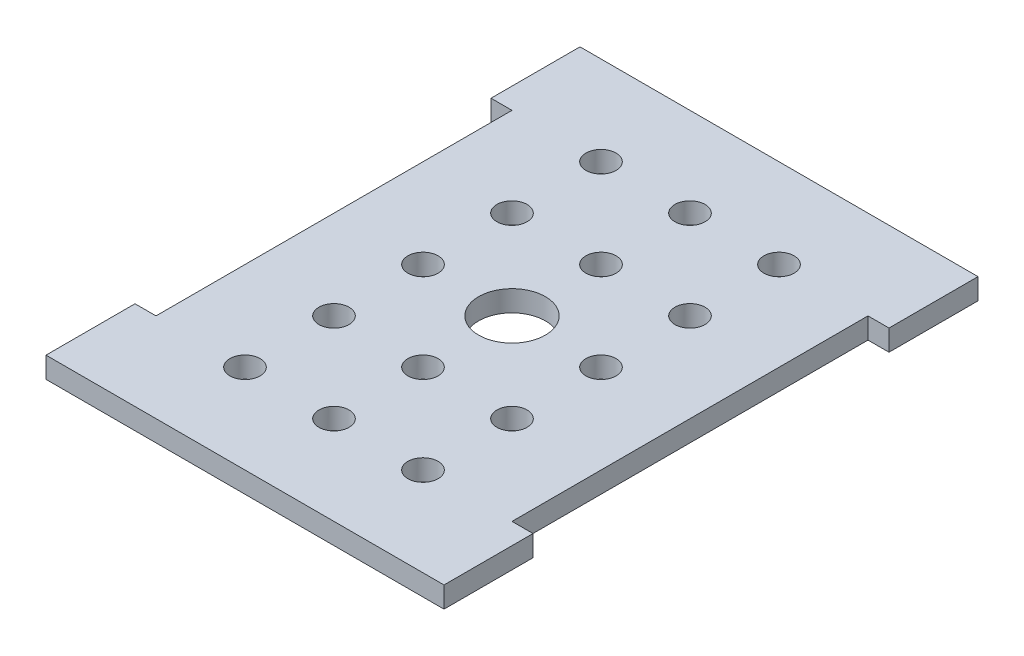
SolidWorks part; units mm, degrees
material "Custom Plastic"
ref_plane "Front Plane" through (0, 0, 0) normal (0, 0, 1) x (1, 0, 0)
ref_plane "Top Plane" through (0, 0, 0) normal (0, 1, 0) x (1, 0, 0)
ref_plane "Right Plane" through (0, 0, 0) normal (1, 0, 0) x (0, 0, -1)
sketch "Sketch1" plane through (0, 0, 0) normal (0, 1, 0) x (1, 0, 0)
  line L1 (-25.4, -38.1) -> (25.4, -38.1)
  line L2 (-25.4, -38.1) -> (-25.4, 38.1)
  line L3 (-25.4, 38.1) -> (25.4, 38.1)
  line L4 (25.4, -38.1) -> (25.4, 38.1)
  line L5 (-25.4, -38.1) -> (25.4, 38.1) construction
  line L6 (-25.4, 38.1) -> (25.4, -38.1) construction
  point P0 (0, 0)
  dimension "D1" = 50.8
  dimension "D2" = 76.2
extrude "Boss-Extrude1" add sketch "Sketch1" along normal blind 2.9972
sketch "Sketch2" plane through (0, 2.9972, 0) normal (0, 1, 0) x (1, 0, 0)
  line L0 (-25.4, 0) -> (25.4, 0) construction
  line L1 (25.4, 38.1) -> (28.3972, 38.1)
  line L2 (25.4, 38.1) -> (25.4, 25.4)
  line L3 (25.4, 25.4) -> (28.3972, 25.4)
  line L4 (28.3972, 38.1) -> (28.3972, 25.4)
  line L5 (-25.4, 38.1) -> (-25.4, -38.1) construction
  line L6 (25.4, -38.1) -> (25.4, 38.1) construction
  line L7 (0, 38.1) -> (0, -38.1) construction
  line L8 (25.4, 38.1) -> (-25.4, 38.1) construction
  line L9 (-25.4, -38.1) -> (25.4, -38.1) construction
  line L10 (28.3972, -38.1) -> (28.3972, -25.4)
  line L11 (25.4, -25.4) -> (28.3972, -25.4)
  line L12 (25.4, -38.1) -> (25.4, -25.4)
  line L13 (25.4, -38.1) -> (28.3972, -38.1)
  line L14 (-25.4, -38.1) -> (-28.3972, -38.1)
  line L15 (-25.4, -38.1) -> (-25.4, -25.4)
  line L16 (-25.4, -25.4) -> (-28.3972, -25.4)
  line L17 (-28.3972, -38.1) -> (-28.3972, -25.4)
  line L18 (-28.3972, 38.1) -> (-28.3972, 25.4)
  line L19 (-25.4, 25.4) -> (-28.3972, 25.4)
  line L20 (-25.4, 38.1) -> (-25.4, 25.4)
  line L21 (-25.4, 38.1) -> (-28.3972, 38.1)
  dimension "D1" = 2.9972
  dimension "D2" = 12.7
extrude "Boss-Extrude2" add sketch "Sketch2" against normal blind 2.9972
sketch "Sketch3" plane through (0, 2.9972, 0) normal (0, 1, 0) x (1, 0, 0)
  line L0 (0, -38.1) -> (0, 38.1) construction
  line L1 (-28.3972, -38.1) -> (28.3972, -38.1) construction
  line L2 (28.3972, 38.1) -> (-28.3972, 38.1) construction
  line L3 (-25.4, 0) -> (25.4, 0) construction
  line L4 (-25.4, 25.4) -> (-25.4, -25.4) construction
  line L5 (25.4, -25.4) -> (25.4, 25.4) construction
  point P12 (0, 0)
  point P13 (-12.7, -25.4)
  point P15 (-12.7, -12.7)
  point P16 (-12.7, 0)
  point P17 (12.7, 0)
  point P18 (12.7, -12.7)
  point P19 (12.7, -25.4)
  point P20 (0, -12.7)
  point P21 (0, -25.4)
  point P22 (0, 25.4)
  point P23 (0, 12.7)
  point P24 (12.7, 25.4)
  point P25 (12.7, 12.7)
  point P26 (-12.7, 12.7)
  point P27 (-12.7, 25.4)
  dimension "D1" = 2
  dimension "D2" = 3
hole_wizard "#8 Clearance Hole1" positions "Sketch5" profile "Sketch4" hole size "#8" standard "ANSI Inch"
sketch "Sketch5" plane through (0, 2.9972, 0) normal (0, 1, 0) x (1, 0, 0)
  point P0 (12.7, -25.4)
  point P3 (0, -25.4)
  point P6 (-12.7, -25.4)
  point P9 (-12.7, -12.7)
  point P12 (0, -12.7)
  point P18 (12.7, -12.7)
  point P21 (-12.7, 0)
  point P24 (0, 0)
  point P27 (12.7, 0)
  point P30 (12.7, 12.7)
  point P33 (0, 12.7)
  point P36 (-12.7, 12.7)
  point P39 (-12.7, 25.4)
  point P42 (0, 25.4)
  point P45 (12.7, 25.4)
sketch "Sketch4" plane through (12.7, 2.9972, 25.4) normal (1, 0, 0) x (0, 0, 1)
  line L0 (0, 0) -> (0, 6.351)
  line L1 (0, 6.351) -> (2.1526, 6.351)
  line L2 (2.1526, 6.351) -> (2.1526, 0)
  line L5 (2.1526, 0) -> (0, 0)
  line L10 (0, 6.351) -> (-2.1526, 6.351) construction
  line L11 (0, -6.35) -> (0, 107.95) construction
  dimension "Hole Dia." = 4.3053
  dimension "Hole Depth" = 6.351
  dimension "Drill Angle" = 180
sketch "Sketch6" plane through (0, 2.9972, 0) normal (0, 1, 0) x (1, 0, 0)
  circle A0 centre (0, 0) radius 4.7625
  dimension "D1" = 9.525
extrude "Cut-Extrude1" cut sketch "Sketch6" against normal through all
